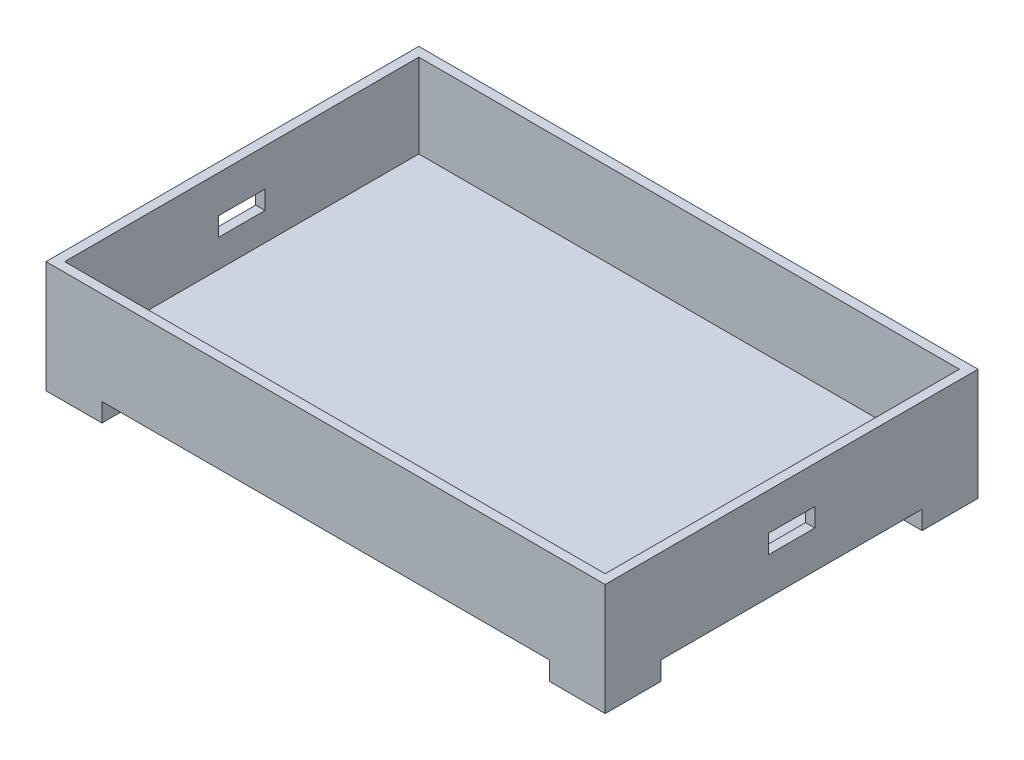
SolidWorks part; units mm, degrees
ref_plane "Front Plane" through (0, 0, 0) normal (0, 0, 1) x (1, 0, 0)
ref_plane "Top Plane" through (0, 0, 0) normal (0, 1, 0) x (1, 0, 0)
ref_plane "Right Plane" through (0, 0, 0) normal (1, 0, 0) x (0, 0, -1)
sketch "Croquis1" plane through (0, 0, 0) normal (0, 1, 0) x (1, 0, 0)
  line L1 (-30, 20) -> (30, 20)
  line L2 (-30, 20) -> (-30, -20)
  line L3 (-30, -20) -> (30, -20)
  line L4 (30, 20) -> (30, -20)
  line L5 (-30, 20) -> (30, -20) construction
  line L6 (-30, -20) -> (30, 20) construction
  point P0 (0, 0)
  dimension "D1" = 60
  dimension "D2" = 40
extrude "Saliente-Extruir1" add sketch "Croquis1" along normal blind 10
shell "Vaciado3" thickness 1
sketch "Croquis3" plane through (-30, 0, 0) normal (-1, 0, 0) x (0, 0, 1)
  line L0 (0, 0) -> (0, 10) construction
  line L1 (-20, 10) -> (20, 10) construction
  line L2 (-20, 5) -> (20, 5) construction
  line L3 (-20, 10) -> (-20, 0) construction
  line L4 (20, 10) -> (20, 0) construction
  line L6 (-2.5, 6) -> (2.5, 6)
  line L7 (-2.5, 6) -> (-2.5, 4)
  line L8 (-2.5, 4) -> (2.5, 4)
  line L9 (2.5, 6) -> (2.5, 4)
  line L10 (-2.5, 6) -> (2.5, 4) construction
  line L11 (-2.5, 4) -> (2.5, 6) construction
  point P11 (0, 5)
  dimension "D1" = 2
  dimension "D2" = 5
extrude "Cortar-Extruir1" cut sketch "Croquis3" against normal through all
sketch "Croquis4" plane through (0, 0, 0) normal (0, -1, 0) x (1, 0, 0)
  line L0 (-30, 20) -> (-30, 14)
  line L1 (-30, -20) -> (-30, 20) construction
  line L2 (-30, 14) -> (-24, 14)
  line L3 (-24, 14) -> (-24, 20)
  line L4 (-30, 20) -> (30, 20) construction
  line L5 (-24, 20) -> (-30, 20)
  line L6 (-30, -20) -> (-24, -20)
  line L8 (30, -20) -> (-30, -20) construction
  line L9 (-24, -20) -> (-24, -14)
  line L10 (-24, -14) -> (-30, -14)
  line L11 (-30, -14) -> (-30, -20)
  line L12 (0, 0) -> (0, 20) construction
  line L13 (24, -14) -> (30, -14)
  line L14 (24, -20) -> (24, -14)
  line L15 (30, -20) -> (24, -20)
  line L16 (30, -14) -> (30, -20)
  line L17 (24, 14) -> (24, 20)
  line L18 (30, 14) -> (24, 14)
  line L19 (30, 20) -> (30, 14)
  line L20 (24, 20) -> (30, 20)
  dimension "D1" = 6
  dimension "D2" = 6
  dimension "D3" = 6
  dimension "D4" = 6
extrude "Saliente-Extruir2" add sketch "Croquis4" along normal blind 2
